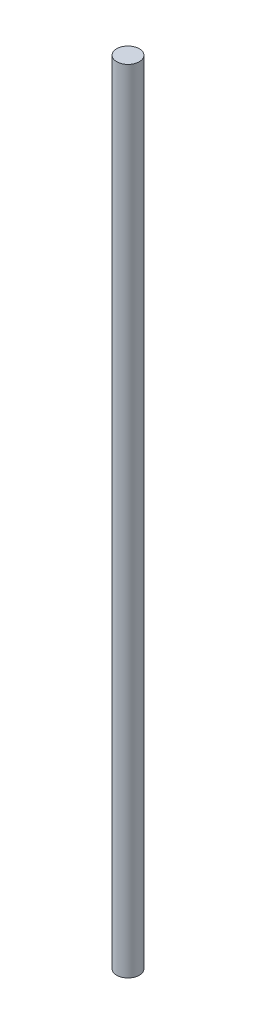
SolidWorks part; units mm, degrees
ref_plane "Front Plane" through (0, 0, 0) normal (0, 0, 1) x (1, 0, 0)
ref_plane "Top Plane" through (0, 0, 0) normal (0, 1, 0) x (1, 0, 0)
ref_plane "Right Plane" through (0, 0, 0) normal (1, 0, 0) x (0, 0, -1)
sketch "Sketch2" plane through (0, 0, 0) normal (0, 1, 0) x (1, 0, 0)
  circle A0 centre (0, 0) radius 4
  dimension "D1" = 8
extrude "Boss-Extrude1" add sketch "Sketch2" along normal blind 280.6
